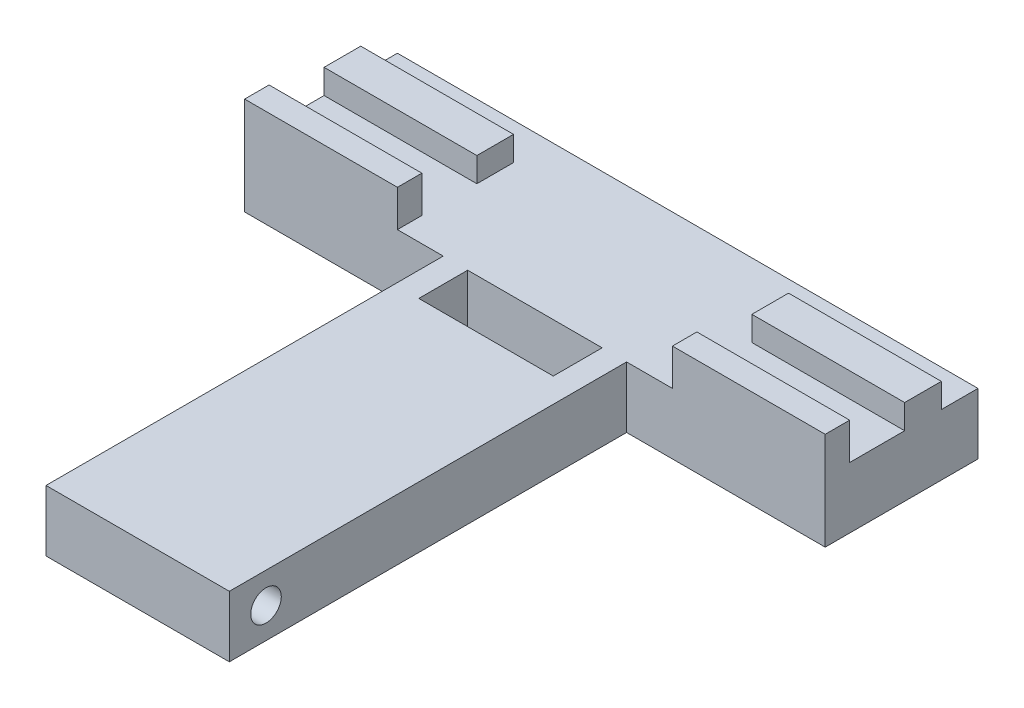
SolidWorks part; units mm, degrees
ref_plane "Front Plane" through (0, 0, 0) normal (0, 0, 1) x (1, 0, 0)
ref_plane "Top Plane" through (0, 0, 0) normal (0, 1, 0) x (1, 0, 0)
ref_plane "Right Plane" through (0, 0, 0) normal (1, 0, 0) x (0, 0, -1)
sketch "Sketch1" plane through (0, 0, 0) normal (0, 1, 0) x (1, 0, 0)
  line L0 (0, 0) -> (0, 6.0822) construction
  line L1 (0, 0) -> (-11.6947, 0) construction
  line L2 (0, 0) -> (15, 0)
  line L3 (15, 0) -> (15, 35)
  line L5 (0, 35) -> (0, 0)
  line L6 (0, 35) -> (-16.25, 35)
  line L7 (-16.25, 35) -> (-16.25, 45)
  line L8 (-16.25, 45) -> (31.25, 45)
  line L9 (31.25, 45) -> (31.25, 35)
  line L10 (31.25, 35) -> (15, 35)
  point P14 (7.1718, 51.0703)
  point P15 (-11.6947, 0)
  dimension "D1" = 47.5
  dimension "D2" = 15
  dimension "D5" = 10
  dimension "D6" = 35
extrude "Boss-Extrude1" add sketch "Sketch1" along normal blind 5
sketch "Sketch2" plane through (15, 0, 0) normal (1, 0, 0) x (0, 0, -1)
  line L0 (0, 0) -> (6.6645, 0) construction
  line L1 (0, 0) -> (35, 0) construction
  line L2 (0, 0) -> (0, 5) construction
  line L3 (0, 5) -> (0, 0) construction
  line L4 (0, 2.5) -> (3, 2.5) construction
  circle A0 centre (3, 2.5) radius 1.25
  dimension "D2" = 2.5
  dimension "D1" = 3
extrude "Cut-Extrude2" cut sketch "Sketch2" against normal through all
sketch "Sketch6" plane through (0, 0, 0) normal (0, -1, 0) x (1, 0, 0)
  line L0 (12.5, -32.5) -> (2.5, -32.5) construction
  line L1 (2, -28.5) -> (13, -28.5)
  line L2 (2, -28.5) -> (2, -32.5)
  line L3 (2, -32.5) -> (13, -32.5)
  line L4 (13, -28.5) -> (13, -32.5)
  line L5 (2, -28.5) -> (13, -32.5) construction
  line L6 (2, -32.5) -> (13, -28.5) construction
  line L7 (0, -35) -> (0, 0) construction
  line L8 (15, 0) -> (15, -35) construction
  line L9 (0, 0) -> (15, 0) construction
  point P5 (7.7971, -31.505)
  point P6 (12.2117, -32.5)
  point P9 (7.2878, -30.6997)
  point P16 (0, 0)
  dimension "D1" = 2
  dimension "D2" = 2
  dimension "D3" = 4
  dimension "D4" = 28.5
extrude "Cut-Extrude3" cut sketch "Sketch6" against normal through all both and the other way through all
sketch "Sketch8" plane through (31.25, 0, 0) normal (1, 0, 0) x (0, 0, -1)
  line L0 (35, 5) -> (45, 5) construction
  line L1 (42, 7) -> (39, 7)
  line L2 (42, 7) -> (42, 5)
  line L3 (42, 5) -> (39, 5)
  line L4 (39, 7) -> (39, 5)
  line L5 (42, 7) -> (39, 5) construction
  line L6 (42, 5) -> (39, 7) construction
  line L7 (35, 5) -> (35, 0) construction
  line L10 (34.5, 8) -> (32.5, 8)
  line L15 (32.5, 0) -> (35, 0)
  line L16 (35, 0) -> (35, 5)
  line L18 (32.5, 8) -> (32.5, 0)
  line L19 (35, 5) -> (34.5, 5)
  line L20 (0, 5) -> (35, 5) construction
  line L21 (34.5, 5) -> (34.5, 8)
  point P0 (40.5, 6)
  dimension "D1" = 4
  dimension "D2" = 2
  dimension "D3" = 3
  dimension "D4" = 2.5
  dimension "D5" = 8
  dimension "D6" = 0.5
extrude "Boss-Extrude4" add sketch "Sketch8" against normal blind 47.5
sketch "Sketch9" plane through (0, 0, -32.5) normal (0, 0, 1) x (1, 0, 0)
  line L1 (18.75, 8) -> (-3.75, 8)
  line L2 (18.75, 8) -> (18.75, 5)
  line L3 (18.75, 5) -> (-3.75, 5)
  line L4 (-3.75, 8) -> (-3.75, 5)
  line L5 (18.75, 8) -> (-3.75, 5) construction
  line L6 (18.75, 5) -> (-3.75, 8) construction
  line L7 (-16.25, 8) -> (31.25, 8) construction
  line L8 (-16.25, 0) -> (31.25, 0) construction
  line L9 (7.5, 0) -> (7.5, 6.5) construction
  point P0 (7.5, 6.5)
  dimension "D1" = 22.5
  dimension "D2" = 3
extrude "Cut-Extrude5" cut sketch "Sketch9" against normal blind 48.5
